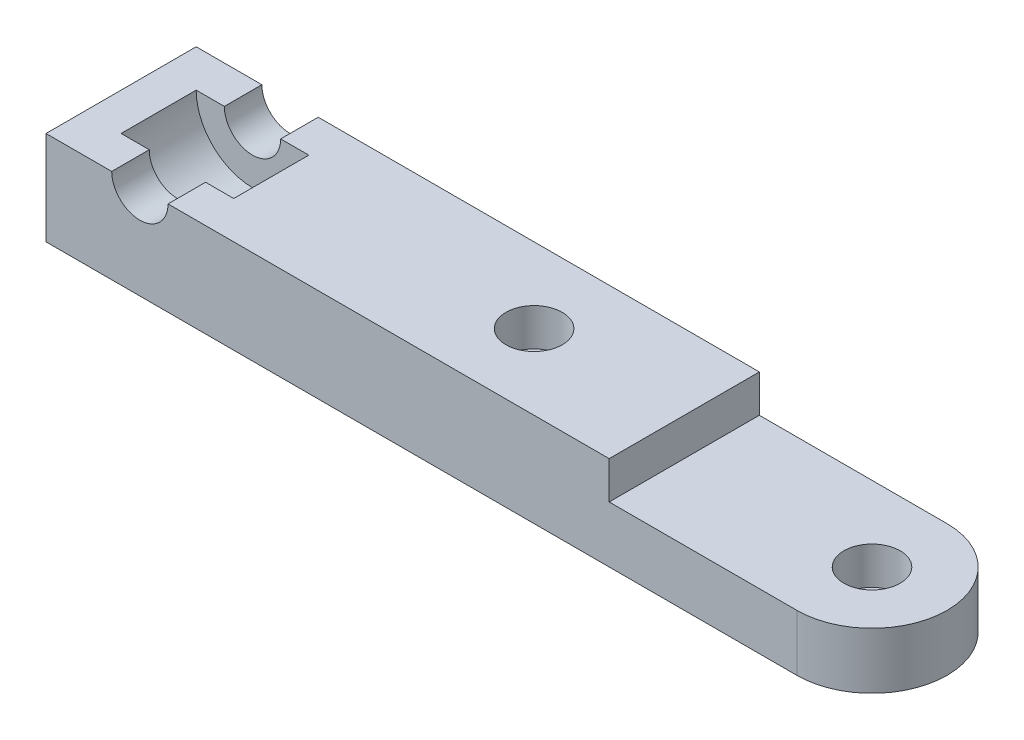
SolidWorks part; units mm, degrees
ref_plane "Front Plane" through (0, 0, 0) normal (0, 0, 1) x (1, 0, 0)
ref_plane "Top Plane" through (0, 0, 0) normal (0, 1, 0) x (1, 0, 0)
ref_plane "Right Plane" through (0, 0, 0) normal (1, 0, 0) x (0, 0, -1)
sketch "Sketch1" plane through (0, 0, 0) normal (0, 1, 0) x (1, 0, 0)
  line L0 (25, -4) -> (65, -4)
  line L1 (65, 4) -> (25, 4)
  line L2 (25, 4) -> (25, -4)
  arc A0 (65, -4) -> (65, 4) centre (65, 0) ccw
  dimension "D3" = 4
  dimension "D1" = 40
  dimension "D2" = 4
extrude "Boss-Extrude2" add sketch "Sketch1" along normal blind 3
sketch "Sketch3" plane through (0, 3, 0) normal (0, 1, 0) x (1, 0, 0)
  line L0 (25, -4) -> (65, -4) construction
  line L1 (25, 4) -> (55, 4)
  line L2 (25, 4) -> (25, -4)
  line L3 (25, -4) -> (55, -4)
  line L4 (55, 4) -> (55, -4)
  dimension "D1" = 30
extrude "Boss-Extrude3" add sketch "Sketch3" along normal blind 2
sketch "Sketch4" plane through (0, 3, 0) normal (0, 1, 0) x (1, 0, 0)
  circle A0 centre (65, 0) radius 1.5
  dimension "D1" = 3
sketch "Sketch12" plane through (0, 5, 0) normal (0, 1, 0) x (1, 0, 0)
  line L0 (55, -4) -> (55, 4) construction
  circle A0 centre (47, 0) radius 1.5
  dimension "D1" = 3
  dimension "D2" = 8
sketch "Sketch13" plane through (0, 0, 4) normal (0, 0, 1) x (1, 0, 0)
  line L0 (25, 5) -> (55, 5) construction
  line L1 (25, 5) -> (25, 0) construction
  line L2 (31.5, 5) -> (28.5, 5)
  arc A0 (31.5, 5) -> (28.5, 5) centre (30, 5) cw
  dimension "D1" = 1.5
  dimension "D2" = 5
extrude "Cut-Extrude1" cut sketch "Sketch13" against normal through all
sketch "Sketch14" plane through (0, 0, 0) normal (0, 0, 1) x (1, 0, 0)
  line L0 (25, 5) -> (28.5, 5) construction
  line L1 (31.5, 5) -> (55, 5) construction
  line L2 (27, 5) -> (33, 5)
  arc A0 (27, 5) -> (33, 5) centre (30, 5) ccw
  dimension "D1" = 3
extrude "Cut-Extrude2" cut sketch "Sketch14" against normal blind 2 and the other way blind 2
extrude "Cut-Extrude3" cut sketch "Sketch4" against normal blind 2
extrude "Cut-Extrude4" cut sketch "Sketch12" against normal blind 2
